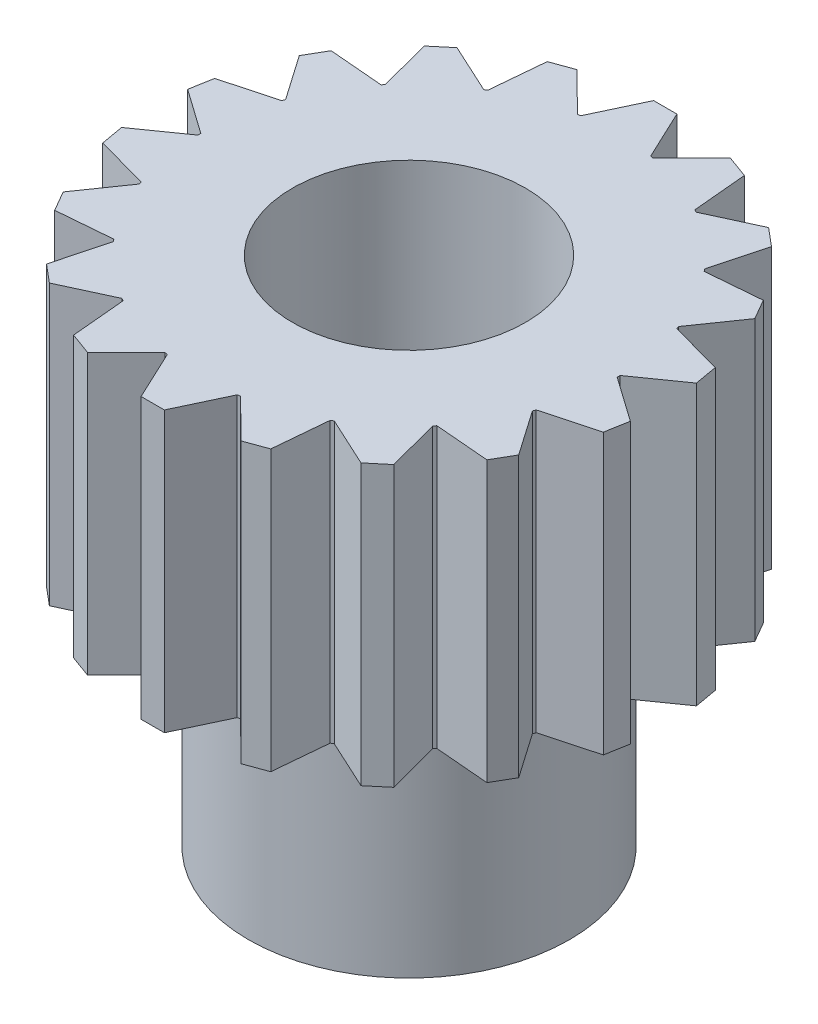
SolidWorks part; units mm, degrees
material "PE High Density Film"
ref_plane "Front" through (0, 0, 0) normal (0, 0, 1) x (1, 0, 0)
ref_plane "Top" through (0, 0, 0) normal (0, 1, 0) x (1, 0, 0)
ref_plane "Right" through (0, 0, 0) normal (1, 0, 0) x (0, 0, -1)
sketch "Sketch1" plane through (0, 0, 0) normal (0, 1, 0) x (1, 0, 0)
  line L0 (0, 2.286) -> (0, -2.794) construction
  circle A0 centre (0, 0) radius 1.27
  circle A2 centre (0, 0) radius 2.286
  dimension "D1" = 2.54
  dimension "D2" = 4.572
extrude "Boss-Extrude1" add sketch "Sketch1" along normal blind 3.048
ref_plane "Plane1" through (0, 3.048, 0) normal (0, 1, 0) x (1, 0, 0)
sketch "Sketch2" plane through (0, 3.048, 0) normal (0, 1, 0) x (1, 0, 0)
  line L0 (0, 2.794) -> (0, -2.286) construction
  line L1 (-0.127, 2.794) -> (0.127, 2.794)
  line L3 (-0.127, 2.794) -> (-0.381, 2.254)
  line L4 (0.127, 2.794) -> (0.381, 2.254)
  arc A0 (0.381, 2.254) -> (-0.381, 2.254) centre (0, 0) ccw
  circle A1 centre (0, 0) radius 2.286 construction
  point P14 (0, 2.254)
  dimension "D1" = 2.794
  dimension "D2" = 0.254
  dimension "D3" = 0.762
extrude "Boss-Extrude2" add sketch "Sketch2" against normal up to surface (3.048 mm away) up to face at (0, 0, 2.286)
pattern_circular "CirPattern2" count 18 over 360 about axis through (0, 0, 0) along (0, 1, 0) of "Boss-Extrude2"
sketch "Sketch3" plane through (0, 0, 0) normal (0, -1, 0) x (-1, 0, 0)
  circle A0 centre (0, 0) radius 1.75
  circle A1 centre (0, 0) radius 1.27
  dimension "D1" = 2.54
  dimension "D2" = 3.5
extrude "Boss-Extrude3" add sketch "Sketch3" along normal blind 2.54
